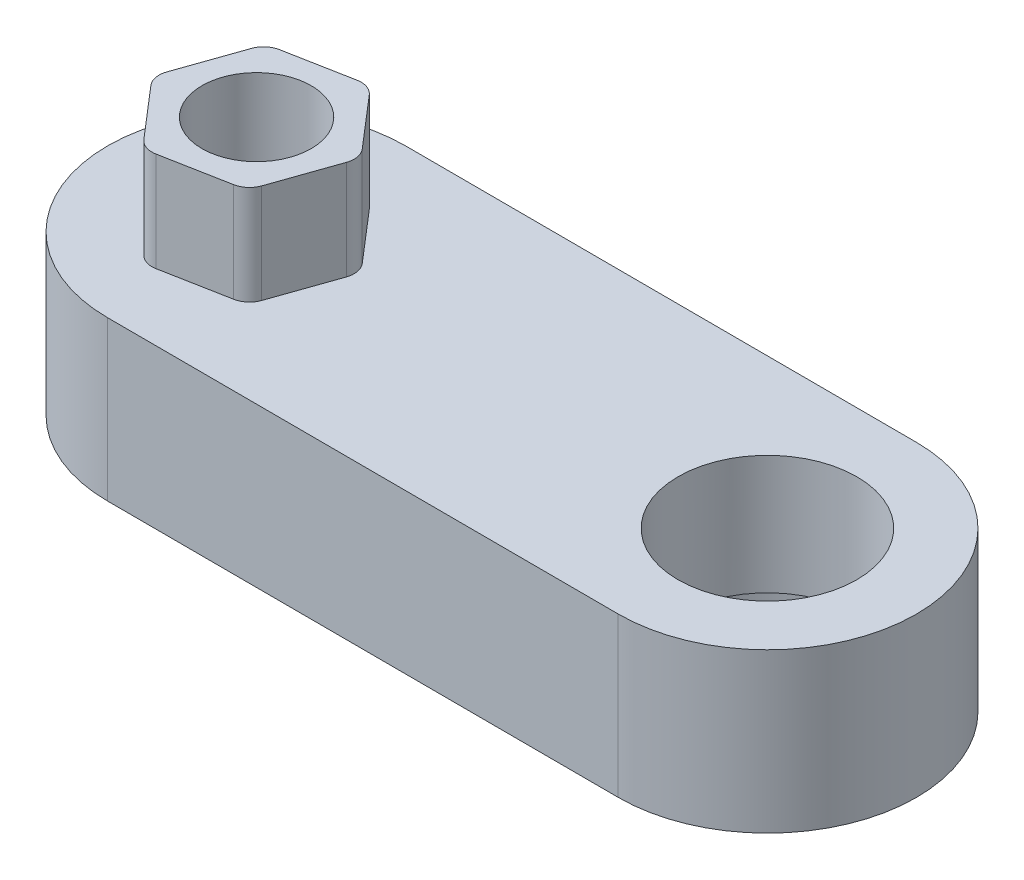
SolidWorks part; units mm, degrees
ref_plane "Front" through (0, 0, 0) normal (0, 0, 1) x (1, 0, 0)
ref_plane "Top" through (0, 0, 0) normal (0, 1, 0) x (1, 0, 0)
ref_plane "Right" through (0, 0, 0) normal (1, 0, 0) x (0, 0, -1)
sketch "Sketch1" plane through (0, 0, 0) normal (0, 1, 0) x (1, 0, 0)
  line L0 (24.0349, 3.3504) -> (-1.7631, 3.4165) construction
  line L1 (24.0156, -4.1496) -> (-1.7823, -4.0835)
  line L2 (24.0541, 10.8503) -> (-1.7439, 10.9165)
  arc A0 (24.0156, -4.1496) -> (24.0541, 10.8503) centre (24.0349, 3.3504) ccw
  arc A1 (-1.7439, 10.9165) -> (-1.7823, -4.0835) centre (-1.7631, 3.4165) ccw
  point P3 (11.1359, 3.3834)
  dimension "D1" = 7.5
extrude "Boss-Extrude1" add sketch "Sketch1" along normal blind 8
sketch "Sketch2" plane through (0, 8, 0) normal (0, 1, 0) x (1, 0, 0)
  line L12 (-3.2518, -0.8337) -> (1.1733, 0.0022)
  line L13 (-6.1882, 2.5806) -> (-3.2518, -0.8337)
  line L14 (-4.6995, 6.8308) -> (-6.1882, 2.5806)
  line L15 (-0.2745, 7.6667) -> (-4.6995, 6.8308)
  line L16 (2.662, 4.2524) -> (-0.2745, 7.6667)
  line L17 (1.1733, 0.0022) -> (2.662, 4.2524)
  line L18 (-3.2518, -0.8337) -> (1.1733, 0.0022)
  line L19 (-6.1882, 2.5806) -> (-3.2518, -0.8337)
  line L20 (-4.6995, 6.8308) -> (-6.1882, 2.5806)
  line L21 (-0.2745, 7.6667) -> (-4.6995, 6.8308)
  line L22 (2.662, 4.2524) -> (-0.2745, 7.6667)
  line L23 (1.1733, 0.0022) -> (2.662, 4.2524)
  dimension "D1" = 0.2
extrude "Boss-Extrude2" add sketch "Sketch2" along normal blind 5
sketch "Sketch3" plane through (0, 13, 0) normal (0, 1, 0) x (1, 0, 0)
  circle A0 centre (-1.7631, 3.4165) radius 2.75
  dimension "D1" = 5.5
extrude "Cut-Extrude1" cut sketch "Sketch3" against normal through all
fillet "Fillet1" radius 1 6 edges at (-4.6995, 10.5, -6.8308) (-0.2745, 10.5, -7.6667) (2.662, 10.5, -4.2524) (-6.1882, 10.5, -2.5806) (-3.2518, 10.5, 0.8337) (1.1733, 10.5, -0.0022)
sketch "Sketch4" plane through (0, 0, 0) normal (0, -1, 0) x (1, 0, 0)
  line L13 (2.943, -3.5422) -> (1.8361, -0.3818)
  line L14 (0.4811, -7.555) -> (2.6646, -5.0161)
  line L15 (-4.225, -7.4293) -> (-0.9346, -8.0508)
  line L16 (-6.4692, -3.2908) -> (-5.3623, -6.4512)
  line L17 (-4.0073, 0.722) -> (-6.1908, -1.8169)
  line L18 (0.6988, 0.5963) -> (-2.5916, 1.2178)
  line L19 (2.943, -3.5422) -> (1.8361, -0.3818)
  line L20 (0.4811, -7.555) -> (2.6646, -5.0161)
  line L21 (-4.225, -7.4293) -> (-0.9346, -8.0508)
  line L22 (-6.4692, -3.2908) -> (-5.3623, -6.4512)
  line L23 (-4.0073, 0.722) -> (-6.1908, -1.8169)
  line L24 (0.6988, 0.5963) -> (-2.5916, 1.2178)
  arc A12 (1.8361, -0.3818) -> (0.6988, 0.5963) centre (0.4204, -0.8777) ccw
  arc A13 (2.6646, -5.0161) -> (2.943, -3.5422) centre (1.5273, -4.0381) ccw
  arc A14 (-0.9346, -8.0508) -> (0.4811, -7.555) centre (-0.6562, -6.5769) ccw
  arc A15 (-5.3623, -6.4512) -> (-4.225, -7.4293) centre (-3.9466, -5.9553) ccw
  arc A16 (-6.1908, -1.8169) -> (-6.4692, -3.2908) centre (-5.0535, -2.795) ccw
  arc A17 (-2.5916, 1.2178) -> (-4.0073, 0.722) centre (-2.87, -0.2561) ccw
  arc A18 (1.8361, -0.3818) -> (0.6988, 0.5963) centre (0.4204, -0.8777) ccw
  arc A19 (2.6646, -5.0161) -> (2.943, -3.5422) centre (1.5273, -4.0381) ccw
  arc A20 (-0.9346, -8.0508) -> (0.4811, -7.555) centre (-0.6562, -6.5769) ccw
  arc A21 (-5.3623, -6.4512) -> (-4.225, -7.4293) centre (-3.9466, -5.9553) ccw
  arc A22 (-6.1908, -1.8169) -> (-6.4692, -3.2908) centre (-5.0535, -2.795) ccw
  arc A23 (-2.5916, 1.2178) -> (-4.0073, 0.722) centre (-2.87, -0.2561) ccw
  dimension "D1" = 0.5
extrude "Cut-Extrude2" cut sketch "Sketch4" against normal blind 3
sketch "Sketch5" plane through (0, 0, 0) normal (0, -1, 0) x (1, 0, 0)
  circle A0 centre (24.0349, -3.3504) radius 6.4 construction
  circle A1 centre (24.0349, -3.3504) radius 6.4 construction
  circle A2 centre (24.0349, -3.3504) radius 6.6
  dimension "D1" = 0.2
extrude "Cut-Extrude3" cut sketch "Sketch5" against normal blind 2 contours A2
sketch "Sketch6" plane through (0, 2, 0) normal (0, -1, 0) x (1, 0, 0)
  circle A0 centre (24.0349, -3.3504) radius 4.5
  dimension "D1" = 9
extrude "Cut-Extrude4" cut sketch "Sketch6" against normal through all
sketch "Sketch7" plane through (0, 8, 0) normal (0, 1, 0) x (1, 0, 0)
  line L0 (23.7646, -6.495) -> (23.5864, -7.4858) construction
  line L1 (34.3301, 7.3589) -> (32.5021, 7.0136) construction
  line L2 (30.5161, 8.3685) -> (29.9087, 11.5837) construction
  line L3 (7.8106, 8.4272) -> (28.7405, 12.3807) construction
  line L4 (9.0008, -8.6487) -> (6.2166, 6.0907) construction
  line L5 (12.5055, -11.0397) -> (13.5948, -10.8339) construction
  line L6 (14.0527, -10.6167) -> (20.916, -4.8458) construction
  line L7 (23.7646, -6.495) -> (23.5864, -7.4858)
  line L8 (34.3301, 7.3589) -> (32.5021, 7.0136)
  line L9 (30.5161, 8.3685) -> (29.9087, 11.5837)
  line L10 (7.8106, 8.4272) -> (28.7405, 12.3807)
  line L11 (9.0008, -8.6487) -> (6.2166, 6.0907)
  line L12 (12.5055, -11.0397) -> (13.5948, -10.8339)
  line L13 (14.0527, -10.6167) -> (20.916, -4.8458)
  arc A0 (23.7646, -6.495) -> (20.916, -4.8458) centre (22.0422, -6.1852) ccw construction
  arc A1 (23.5864, -7.4858) -> (24.8592, -8.6203) centre (24.5706, -7.6629) ccw construction
  arc A2 (24.8592, -8.6203) -> (35.5147, 6.4216) centre (20.5301, 5.7414) ccw construction
  arc A3 (35.5147, 6.4216) -> (34.3301, 7.3589) centre (34.5157, 6.3763) ccw construction
  arc A4 (30.5161, 8.3685) -> (32.5021, 7.0136) centre (32.1865, 8.684) ccw construction
  arc A5 (29.9087, 11.5837) -> (28.7405, 12.3807) centre (28.9261, 11.3981) ccw construction
  arc A6 (7.8106, 8.4272) -> (6.2166, 6.0907) centre (8.1818, 6.4619) ccw construction
  arc A7 (9.0008, -8.6487) -> (12.5055, -11.0397) centre (11.9487, -8.0918) ccw construction
  arc A8 (13.5948, -10.8339) -> (14.0527, -10.6167) centre (13.4091, -9.8513) ccw construction
  arc A9 (23.7646, -6.495) -> (20.916, -4.8458) centre (22.0422, -6.1852) ccw
  arc A10 (23.5864, -7.4858) -> (24.8592, -8.6203) centre (24.5706, -7.6629) ccw
  arc A11 (24.8592, -8.6203) -> (35.5147, 6.4216) centre (20.5301, 5.7414) ccw
  arc A12 (35.5147, 6.4216) -> (34.3301, 7.3589) centre (34.5157, 6.3763) ccw
  arc A13 (30.5161, 8.3685) -> (32.5021, 7.0136) centre (32.1865, 8.684) ccw
  arc A14 (29.9087, 11.5837) -> (28.7405, 12.3807) centre (28.9261, 11.3981) ccw
  arc A15 (7.8106, 8.4272) -> (6.2166, 6.0907) centre (8.1818, 6.4619) ccw
  arc A16 (9.0008, -8.6487) -> (12.5055, -11.0397) centre (11.9487, -8.0918) ccw
  arc A17 (13.5948, -10.8339) -> (14.0527, -10.6167) centre (13.4091, -9.8513) ccw
sketch "Sketch8" plane through (0, 8, 0) normal (0, 1, 0) x (1, 0, 0)
  line L9 (17.2913, -7.5016) -> (23.8816, -7.539)
  line L10 (29.3206, 11.9763) -> (33.1795, 10.7177)
  line L11 (33.1795, 10.7177) -> (34.3858, 7.0641)
  line L16 (12.4498, -10.7449) -> (13.5391, -10.5391)
  line L17 (6.5114, 6.1464) -> (9.2956, -8.593)
  line L18 (28.7962, 12.0859) -> (7.8663, 8.1324)
  line L19 (30.2213, 8.3128) -> (29.6139, 11.528)
  line L20 (34.3858, 7.0641) -> (32.5577, 6.7188)
  line L21 (24.0599, -6.5481) -> (23.8816, -7.539)
  line L22 (13.8596, -10.3871) -> (20.7229, -4.6161)
  line L26 (30.2213, 8.3128) -> (29.6139, 11.528)
  line L27 (34.3858, 7.0641) -> (32.5577, 6.7188)
  line L28 (24.0599, -6.5481) -> (23.8816, -7.539)
  line L29 (17.2913, -7.5016) -> (20.7229, -4.6161)
  arc A20 (13.5391, -10.5391) -> (13.8596, -10.3871) centre (13.4091, -9.8513) ccw
  arc A21 (9.2956, -8.593) -> (12.4498, -10.7449) centre (11.9487, -8.0918) ccw
  arc A22 (7.8663, 8.1324) -> (6.5114, 6.1464) centre (8.1818, 6.4619) ccw
  arc A23 (29.6139, 11.528) -> (28.7962, 12.0859) centre (28.9261, 11.3981) ccw
  arc A24 (30.2213, 8.3128) -> (32.5577, 6.7188) centre (32.1865, 8.684) ccw
  arc A25 (35.215, 6.408) -> (34.3858, 7.0641) centre (34.5157, 6.3763) ccw
  arc A26 (24.7726, -8.3331) -> (35.215, 6.408) centre (20.5301, 5.7414) ccw
  arc A27 (23.8816, -7.539) -> (24.7726, -8.3331) centre (24.5706, -7.6629) ccw
  arc A28 (24.0599, -6.5481) -> (20.7229, -4.6161) centre (22.0422, -6.1852) ccw
  arc A32 (29.6139, 11.528) -> (29.3206, 11.9763) centre (28.9261, 11.3981) ccw
  arc A33 (30.2213, 8.3128) -> (32.5577, 6.7188) centre (32.1865, 8.684) ccw
  arc A37 (24.0599, -6.5481) -> (20.7229, -4.6161) centre (22.0422, -6.1852) ccw
  dimension "D1" = 0.3
extrude "Cut-Extrude5" [suppressed] cut sketch "Sketch8" against normal up to surface (8 mm away)
fillet "Fillet2" [suppressed] radius 2
